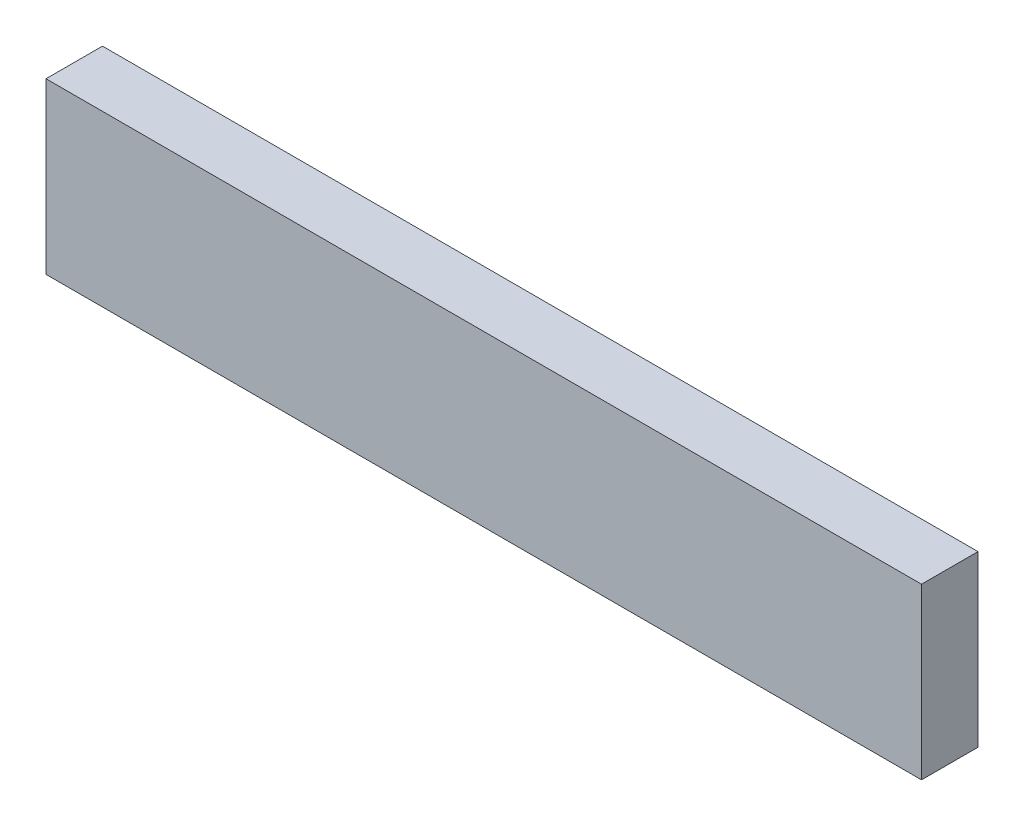
SolidWorks part; units mm, degrees
ref_plane "前视基准面" through (0, 0, 0) normal (0, 0, 1) x (1, 0, 0)
ref_plane "上视基准面" through (0, 0, 0) normal (0, 1, 0) x (1, 0, 0)
ref_plane "右视基准面" through (0, 0, 0) normal (1, 0, 0) x (0, 0, -1)
other "Configuration Table"
sketch "草图1" plane through (0, 0, 0) normal (0, 0, 1) x (1, 0, 0)
  line L1 (-155, -30) -> (155, -30)
  line L2 (-155, -30) -> (-155, 30)
  line L3 (-155, 30) -> (155, 30)
  line L4 (155, -30) -> (155, 30)
  line L5 (-155, -30) -> (155, 30) construction
  line L6 (-155, 30) -> (155, -30) construction
  point P0 (0, 0)
extrude "凸台-拉伸1" add sketch "草图1" along normal blind 20
